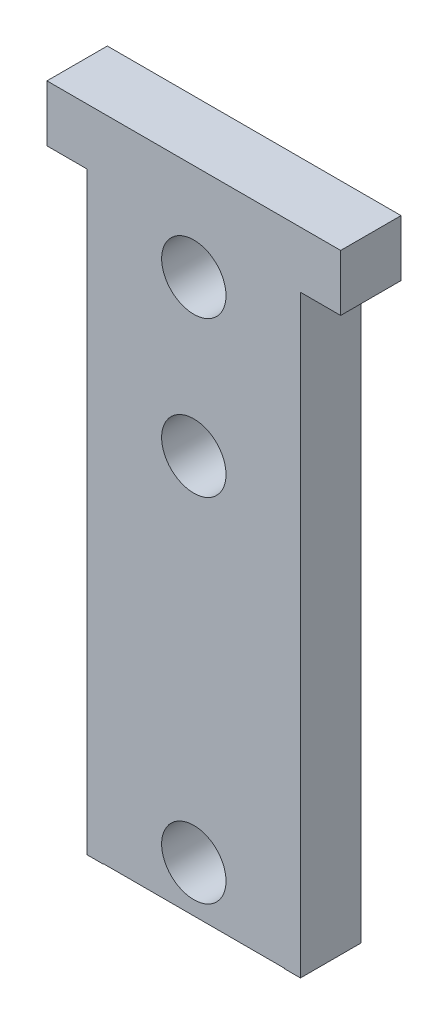
SolidWorks part; units mm, degrees
ref_plane "Ebene vorne" through (0, 0, 0) normal (0, 0, 1) x (1, 0, 0)
ref_plane "Ebene oben" through (0, 0, 0) normal (0, 1, 0) x (1, 0, 0)
ref_plane "Ebene rechts" through (0, 0, 0) normal (1, 0, 0) x (0, 0, -1)
sketch "Skizze1" plane through (0, 0, 0) normal (0, 0, 1) x (1, 0, 0)
  line L1 (-3.5, -16.25) -> (3.5, -16.25)
  line L2 (-3.5, -16.25) -> (-3.5, 16.25)
  line L3 (-3.5, 16.25) -> (3.5, 16.25)
  line L4 (3.5, -16.25) -> (3.5, 16.25)
  line L5 (-3.5, -16.25) -> (3.5, 16.25) construction
  line L6 (-3.5, 16.25) -> (3.5, -16.25) construction
  line L7 (-3.5, 16.25) -> (6, 16.25)
  line L8 (-3.5, 16.25) -> (-3.5, 13.25)
  line L9 (-3.5, 13.25) -> (6, 13.25)
  line L10 (6, 16.25) -> (6, 13.25)
  line L11 (3.5, 16.25) -> (-6, 16.25)
  line L12 (3.5, 16.25) -> (3.5, 13.25)
  line L13 (3.5, 13.25) -> (-6, 13.25)
  line L14 (-6, 16.25) -> (-6, 13.25)
  line L15 (3.5, 16.25) -> (-3.5, 16.25)
  line L16 (3.5, 16.25) -> (3.5, 6.25)
  line L17 (3.5, 6.25) -> (-3.5, 6.25)
  line L18 (-3.5, 16.25) -> (-3.5, 6.25)
  circle A0 centre (0, -13.95) radius 1.5
  circle A1 centre (0, 3.55) radius 1.5
  circle A2 centre (0, 11.25) radius 1.25
  point P0 (0, 0)
  dimension "D7" = 3
  dimension "D8" = 3
  dimension "D13" = 2.5
  dimension "D1" = 32.5
  dimension "D2" = 7
  dimension "D3" = 3
  dimension "D4" = 3
  dimension "D5" = 12
  dimension "D6" = 2.5
  dimension "D9" = 17.5
  dimension "D10" = 2.3
  dimension "D11" = 10
  dimension "D12" = 22.5
  dimension "D14" = 5
extrude "Aufsatz-Linear austragen1" add sketch "Skizze1" along normal blind 3 contours L10 L7 L4 L9 | L2 L9 L4 L3 | L11 L14 L13 L2 | L17 L4 L9 L2 A2 | L4 L17 L2 L1 A1 A0
sketch "Skizze2" plane through (0, 0, 0) normal (0, 0, -1) x (-1, 0, 0)
  line L1 (-3.5, -16.25) -> (-5.5, -16.25)
  line L2 (-3.5, -16.25) -> (-3.5, 14.1331)
  line L3 (-3.5, 14.1331) -> (-5.5, 14.1331)
  line L4 (-5.5, -16.25) -> (-5.5, 14.1331)
  line L5 (3.5, -16.25) -> (5.5, -16.25)
  line L6 (3.5, -16.25) -> (3.5, 14.1331)
  line L7 (3.5, 14.1331) -> (5.5, 14.1331)
  line L8 (5.5, -16.25) -> (5.5, 14.1331)
  line L9 (-7.5, 16.25) -> (7.5, 16.25)
  line L10 (-7.5, 16.25) -> (-7.5, 13.25)
  line L11 (-7.5, 13.25) -> (7.5, 13.25)
  line L12 (7.5, 16.25) -> (7.5, 13.25)
  line M9 (-6, 16.25) -> (-6, 13.25)
  line M10 (-6, 13.25) -> (-3.5, 13.25)
  line M11 (-3.5, 13.25) -> (-3.5, -16.25)
  line M13 (3.5, -16.25) -> (3.5, 13.25)
  line M14 (3.5, 13.25) -> (6, 13.25)
  line M15 (6, 13.25) -> (6, 16.25)
  dimension "D1" = 2
  dimension "D2" = 2
  dimension "D3" = 2
  dimension "D4" = 2
extrude "Aufsatz-Linear austragen2" add sketch "Skizze2" against normal blind 3 contours L4 L1 M11 M10 | L5 L8 M14 M13 | L12 L9 L11 M15 | L10 L11 L9 M9
sketch "Skizze3" plane through (0, 0, 3) normal (0, 0, 1) x (1, 0, 0)
  line L0 (-5.5, -16.25) -> (5.5, -16.25) construction
  line L1 (-5.5, 13.25) -> (-4.5, 13.25)
  line L2 (-5.5, 13.25) -> (-5.5, -16.25)
  line L3 (-5.5, -16.25) -> (-4.5, -16.25)
  line L4 (-4.5, 13.25) -> (-4.5, -16.25)
  line L5 (5.5, 13.25) -> (7.5, 13.25) construction
  line L6 (5.5, 13.25) -> (4.5, 13.25)
  line L7 (5.5, 13.25) -> (5.5, -16.25)
  line L8 (5.5, -16.25) -> (4.5, -16.25)
  line L9 (4.5, 13.25) -> (4.5, -16.25)
  line L10 (7.5, 16.25) -> (6.5, 16.25)
  line L11 (7.5, 16.25) -> (7.5, 13.25)
  line L12 (7.5, 13.25) -> (6.5, 13.25)
  line L13 (6.5, 16.25) -> (6.5, 13.25)
  line L14 (-5.5, 13.25) -> (-7.5, 13.25) construction
  line L15 (-7.5, 16.25) -> (-6.5, 16.25)
  line L16 (-7.5, 16.25) -> (-7.5, 13.25)
  line L17 (-7.5, 13.25) -> (-6.5, 13.25)
  line L18 (-6.5, 16.25) -> (-6.5, 13.25)
  line L21 (-7.5, 16.25) -> (7.5, 16.25)
  line L22 (-7.5, 16.25) -> (-7.5, 15.25)
  line L23 (-7.5, 15.25) -> (7.5, 15.25)
  line L24 (7.5, 16.25) -> (7.5, 15.25)
  line M7 (5.5, -16.25) -> (5.5, 13.25)
  line M8 (5.5, 13.25) -> (7.5, 13.25)
  line M9 (7.5, 13.25) -> (7.5, 16.25)
  line M10 (7.5, 16.25) -> (-7.5, 16.25)
  line M11 (-7.5, 16.25) -> (-7.5, 13.25)
  line M12 (-7.5, 13.25) -> (-5.5, 13.25)
  line M13 (-5.5, 13.25) -> (-5.5, -16.25)
  line M14 (-5.5, -16.25) -> (5.5, -16.25)
  dimension "D1" = 1
  dimension "D2" = 1
  dimension "D3" = 1
  dimension "D4" = 1
  dimension "D5" = 1
extrude "Schnitt-Linear austragen1" cut sketch "Skizze3" against normal blind 10 contours L23 L18 M11 M10 | L23 L16 L18 M12 | L18 L23 L13 M10 | L13 L23 L11 M10 | L23 L13 M8 M9 | L6 L9 M14 M7 | L4 L1 M13 M14
sketch "Skizze4" plane through (0, 0, 3) normal (0, 0, 1) x (1, 0, 0)
  line L0 (-6.5, 15.25) -> (6.5, 15.25) construction
  line L1 (-6.5, 15.25) -> (-7.3, 15.25)
  line L2 (-6.5, 15.25) -> (-6.5, 13.2507)
  line L3 (-6.5, 13.2507) -> (-7.3, 13.2507)
  line L4 (-7.3, 15.25) -> (-7.3, 13.2507)
  line L5 (-4.5, 13.25) -> (-5.3, 13.25)
  line L6 (-4.5, 13.25) -> (-4.5, -16.2712)
  line L7 (-4.5, -16.2712) -> (-5.3, -16.2712)
  line L8 (-5.3, 13.25) -> (-5.3, -16.2712)
  line L9 (4.5, 13.25) -> (5.3, 13.25)
  line L10 (4.5, 13.25) -> (4.5, -16.2712)
  line L11 (4.5, -16.2712) -> (5.3, -16.2712)
  line L12 (5.3, 13.25) -> (5.3, -16.2712)
  line L13 (6.5, 13.25) -> (7.3, 13.25)
  line L14 (6.5, 13.25) -> (6.5, 15.25)
  line L15 (6.5, 15.25) -> (7.3, 15.25)
  line L16 (7.3, 13.25) -> (7.3, 15.25)
  line L17 (7.3, 15.25) -> (-7.3, 15.25)
  line L18 (7.3, 15.25) -> (7.3, 16.05)
  line L19 (7.3, 16.05) -> (-7.3, 16.05)
  line L20 (-7.3, 15.25) -> (-7.3, 16.05)
  line M9 (-6.5, 13.25) -> (-4.5, 13.25)
  line M10 (-4.5, 13.25) -> (-4.5, -16.25)
  line M12 (4.5, -16.25) -> (4.5, 13.25)
  line M13 (4.5, 13.25) -> (6.5, 13.25)
  line M14 (6.5, 13.25) -> (6.5, 15.25)
  line M15 (6.5, 15.25) -> (-6.5, 15.25)
  line M16 (-6.5, 15.25) -> (-6.5, 13.25)
  dimension "D1" = 0.8
  dimension "D2" = 0.8
  dimension "D3" = 0.8
  dimension "D4" = 0.8
  dimension "D5" = 0.8
extrude "Aufsatz-Linear austragen3" add sketch "Skizze4" against normal blind 3 contours L20 L1 L15 L18 L19 M15 | L1 L4 L3 M16 | L8 L7 L6 M9 M10 | L12 L10 L11 M13 M12 | L13 L16 L15 M14
sketch "Skizze5" plane through (0, 0, 3) normal (0, 0, 1) x (1, 0, 0)
  circle A1 centre (0, 11.25) radius 1.6
  circle A3 centre (0, 3.55) radius 1.6
  circle A4 centre (0, -13.95) radius 1.6
  dimension "D1" = 3.2
  dimension "D2" = 3.2
  dimension "D3" = 3.2
extrude "Schnitt-Linear austragen2" cut sketch "Skizze5" against normal blind 3
